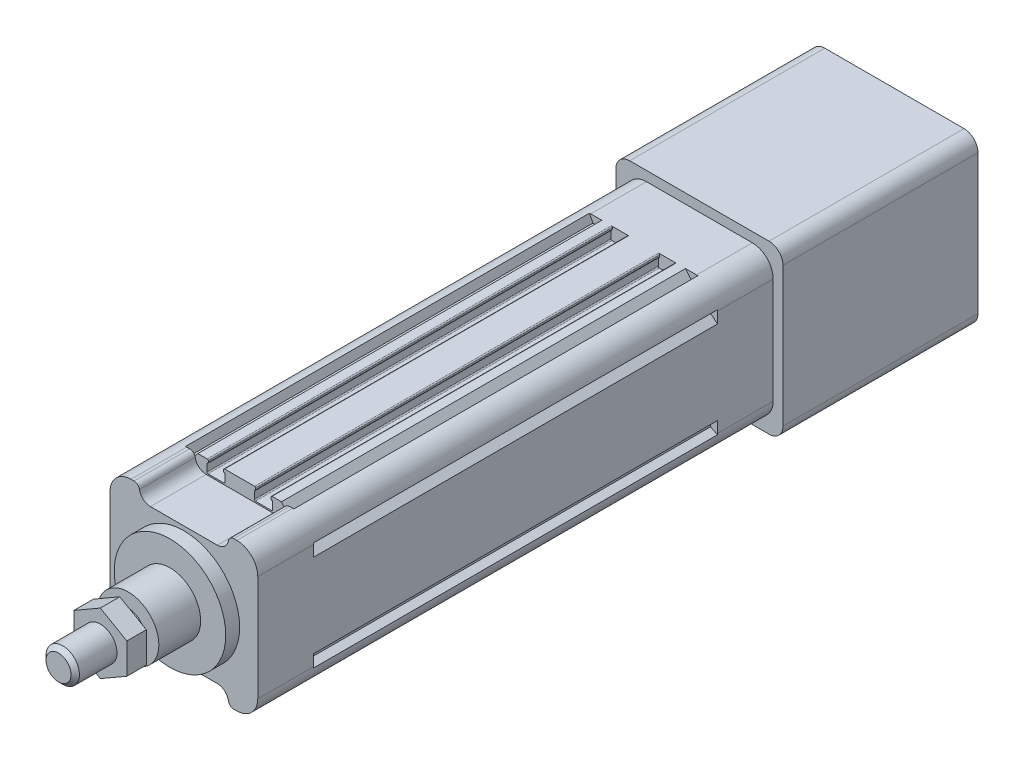
SolidWorks part; units mm, degrees
ref_plane "Front" through (0, 0, 0) normal (0, 0, 1) x (1, 0, 0)
ref_plane "Top" through (0, 0, 0) normal (0, 1, 0) x (1, 0, 0)
ref_plane "Right" through (0, 0, 0) normal (1, 0, 0) x (0, 0, -1)
sketch "草图1" plane through (0, 0, 0) normal (0, 0, 1) x (1, 0, 0)
  line L0 (19.7737, 3) -> (23.3, 3)
  line L1 (23.3, 3) -> (23.3, -3)
  line L2 (23.3, -3) -> (19.7737, -3)
  line L3 (-19.7737, -3) -> (-23.3, -3)
  line L4 (-23.3, -3) -> (-23.3, 3)
  line L5 (-23.3, 3) -> (-19.7737, 3)
  line L6 (-18.2, 24) -> (-19.4434, 26.4869)
  line L7 (-26.4869, 19.4434) -> (-24, 18.2)
  line L8 (-24, 18.2) -> (-24, 17.1)
  line L9 (-24, 17.1) -> (-26.5, 15)
  line L10 (-26.5, 15) -> (-26.5, -15)
  line L11 (-26.5, -15) -> (-24, -17.1)
  line L12 (-24, -17.1) -> (-24, -18.2)
  line L13 (-24, -18.2) -> (-26.4869, -19.4434)
  line L14 (-19.4434, -26.4869) -> (-18.2, -24)
  line L15 (-18.2, -24) -> (-17.1, -24)
  line L16 (-17.1, -24) -> (-15, -26.5)
  line L17 (-15, -26.5) -> (-11.65, -26.5)
  line L18 (-11.25, -26.1) -> (-11.25, -25.6)
  line L19 (-11.65, -25.2) -> (-11.75, -25.2)
  line L20 (-11.75, -25.2) -> (-11.75, -22.4)
  line L21 (-11.35, -22) -> (-5.65, -22)
  line L22 (-5.25, -22.4) -> (-5.25, -25.2)
  line L23 (-5.25, -25.2) -> (-5.35, -25.2)
  line L24 (-5.75, -25.6) -> (-5.75, -26.1)
  line L25 (-5.35, -26.5) -> (5.35, -26.5)
  line L26 (5.75, -26.1) -> (5.75, -25.6)
  line L27 (5.35, -25.2) -> (5.25, -25.2)
  line L28 (5.25, -25.2) -> (5.25, -22.4)
  line L29 (5.65, -22) -> (11.35, -22)
  line L30 (11.75, -22.4) -> (11.75, -25.2)
  line L31 (11.75, -25.2) -> (11.65, -25.2)
  line L32 (11.25, -25.6) -> (11.25, -26.1)
  line L33 (11.65, -26.5) -> (15, -26.5)
  line L34 (15, -26.5) -> (17.1, -24)
  line L35 (17.1, -24) -> (18.2, -24)
  line L36 (18.2, -24) -> (19.4434, -26.4869)
  line L37 (26.4869, -19.4434) -> (24, -18.2)
  line L38 (24, -18.2) -> (24, -17.1)
  line L39 (24, -17.1) -> (26.5, -15)
  line L40 (26.5, -15) -> (26.5, 15)
  line L41 (26.5, 15) -> (24, 17.1)
  line L42 (24, 17.1) -> (24, 18.2)
  line L43 (24, 18.2) -> (26.4869, 19.4434)
  line L44 (19.4434, 26.4869) -> (18.2, 24)
  line L45 (18.2, 24) -> (17.1, 24)
  line L46 (17.1, 24) -> (15, 26.5)
  line L47 (15, 26.5) -> (11.65, 26.5)
  line L48 (11.25, 26.1) -> (11.25, 25.6)
  line L49 (11.65, 25.2) -> (11.75, 25.2)
  line L50 (11.75, 25.2) -> (11.75, 22.4)
  line L51 (11.35, 22) -> (5.65, 22)
  line L52 (5.25, 22.4) -> (5.25, 25.2)
  line L53 (5.25, 25.2) -> (5.35, 25.2)
  line L54 (5.75, 25.6) -> (5.75, 26.1)
  line L55 (5.35, 26.5) -> (-5.35, 26.5)
  line L56 (-5.75, 26.1) -> (-5.75, 25.6)
  line L57 (-5.35, 25.2) -> (-5.25, 25.2)
  line L58 (-5.25, 25.2) -> (-5.25, 22.4)
  line L59 (-5.65, 22) -> (-11.35, 22)
  line L60 (-11.75, 22.4) -> (-11.75, 25.2)
  line L61 (-11.75, 25.2) -> (-11.65, 25.2)
  line L62 (-11.25, 25.6) -> (-11.25, 26.1)
  line L63 (-11.65, 26.5) -> (-15, 26.5)
  line L64 (-15, 26.5) -> (-17.1, 24)
  line L65 (-17.1, 24) -> (-18.2, 24)
  arc A0 (19.7737, 3) -> (-19.7737, 3) centre (0, 0) ccw
  arc A1 (-19.7737, -3) -> (19.7737, -3) centre (0, 0) ccw
  circle A2 centre (19, 19) radius 2.1
  circle A3 centre (19, -19) radius 2.1
  circle A4 centre (-19, -19) radius 2.1
  circle A5 centre (-19, 19) radius 2.1
  arc A6 (-19.4434, 26.4869) -> (-26.4869, 19.4434) centre (-19, 19) ccw
  arc A7 (-26.4869, -19.4434) -> (-19.4434, -26.4869) centre (-19, -19) ccw
  arc A8 (-11.65, -26.5) -> (-11.25, -26.1) centre (-11.65, -26.1) ccw
  arc A9 (-11.25, -25.6) -> (-11.65, -25.2) centre (-11.65, -25.6) ccw
  arc A10 (-11.35, -22) -> (-11.75, -22.4) centre (-11.35, -22.4) ccw
  arc A11 (-5.25, -22.4) -> (-5.65, -22) centre (-5.65, -22.4) ccw
  arc A12 (-5.35, -25.2) -> (-5.75, -25.6) centre (-5.35, -25.6) ccw
  arc A13 (-5.75, -26.1) -> (-5.35, -26.5) centre (-5.35, -26.1) ccw
  arc A14 (5.35, -26.5) -> (5.75, -26.1) centre (5.35, -26.1) ccw
  arc A15 (5.75, -25.6) -> (5.35, -25.2) centre (5.35, -25.6) ccw
  arc A16 (5.65, -22) -> (5.25, -22.4) centre (5.65, -22.4) ccw
  arc A17 (11.75, -22.4) -> (11.35, -22) centre (11.35, -22.4) ccw
  arc A18 (11.65, -25.2) -> (11.25, -25.6) centre (11.65, -25.6) ccw
  arc A19 (11.25, -26.1) -> (11.65, -26.5) centre (11.65, -26.1) ccw
  arc A20 (19.4434, -26.4869) -> (26.4869, -19.4434) centre (19, -19) ccw
  arc A21 (26.4869, 19.4434) -> (19.4434, 26.4869) centre (19, 19) ccw
  arc A22 (11.65, 26.5) -> (11.25, 26.1) centre (11.65, 26.1) ccw
  arc A23 (11.25, 25.6) -> (11.65, 25.2) centre (11.65, 25.6) ccw
  arc A24 (11.35, 22) -> (11.75, 22.4) centre (11.35, 22.4) ccw
  arc A25 (5.25, 22.4) -> (5.65, 22) centre (5.65, 22.4) ccw
  arc A26 (5.35, 25.2) -> (5.75, 25.6) centre (5.35, 25.6) ccw
  arc A27 (5.75, 26.1) -> (5.35, 26.5) centre (5.35, 26.1) ccw
  arc A28 (-5.35, 26.5) -> (-5.75, 26.1) centre (-5.35, 26.1) ccw
  arc A29 (-5.75, 25.6) -> (-5.35, 25.2) centre (-5.35, 25.6) ccw
  arc A30 (-5.65, 22) -> (-5.25, 22.4) centre (-5.65, 22.4) ccw
  arc A31 (-11.75, 22.4) -> (-11.35, 22) centre (-11.35, 22.4) ccw
  arc A32 (-11.65, 25.2) -> (-11.25, 25.6) centre (-11.65, 25.6) ccw
  arc A33 (-11.25, 26.1) -> (-11.65, 26.5) centre (-11.65, 26.1) ccw
extrude "凸台-拉伸1" add sketch "草图1" along normal blind 145
sketch "草图6" plane through (0, 0, 145) normal (0, 0, 1) x (1, 0, 0)
  line L0 (0, 0) -> (19, 0) construction
  line L2 (-26.5, -19) -> (-26.5, 19)
  line L3 (-19, 26.5) -> (-17.9161, 26.5)
  line L4 (26.5, -19) -> (26.5, 19)
  line L5 (-26.5, -26.5) -> (26.5, 26.5) construction
  line L6 (-26.5, 26.5) -> (26.5, -26.5) construction
  line L7 (-12, 21.5) -> (12, 21.5)
  line L9 (19, 26.5) -> (17.9161, 26.5)
  line L10 (19, -26.5) -> (17.9161, -26.5)
  line L11 (-12, -21.5) -> (12, -21.5)
  line L12 (-19, -26.5) -> (-17.9161, -26.5)
  arc A0 (12, 21.5) -> (15.9441, 24.8333) centre (12, 25.5) ccw
  arc A1 (-15.9441, 24.8333) -> (-12, 21.5) centre (-12, 25.5) ccw
  arc A2 (-15.9441, 24.8333) -> (-17.9161, 26.5) centre (-17.9161, 24.5) ccw
  arc A3 (15.9441, 24.8333) -> (17.9161, 26.5) centre (17.9161, 24.5) cw
  arc A4 (-26.5, -19) -> (-19, -26.5) centre (-19, -19) ccw
  arc A5 (19, -26.5) -> (26.5, -19) centre (19, -19) ccw
  arc A6 (26.5, 19) -> (19, 26.5) centre (19, 19) ccw
  arc A7 (-26.5, 19) -> (-19, 26.5) centre (-19, 19) cw
  arc A8 (15.9441, -24.8333) -> (17.9161, -26.5) centre (17.9161, -24.5) ccw
  arc A9 (12, -21.5) -> (15.9441, -24.8333) centre (12, -25.5) cw
  arc A10 (-15.9441, -24.8333) -> (-12, -21.5) centre (-12, -25.5) cw
  arc A11 (-15.9441, -24.8333) -> (-17.9161, -26.5) centre (-17.9161, -24.5) cw
  point P0 (0, 0)
  point P9 (0, 21.5)
  point P13 (20, 20.8461)
  point P16 (-12, 20.8461)
  dimension "D5" = 4
  dimension "D6" = 2
  dimension "D7" = 2
  dimension "D9" = 7.5
  dimension "D1" = 53
  dimension "D2" = 53
  dimension "D3" = 26.5
  dimension "D4" = 24
  dimension "D8" = 5
extrude "凸台-拉伸2" add sketch "草图6" along normal blind 20
sketch "草图7" plane through (0, 0, 165) normal (0, 0, 1) x (1, 0, 0)
  circle A0 centre (0, 0) radius 20
  dimension "D1" = 40
extrude "凸台-拉伸3" add sketch "草图7" along normal blind 5
sketch "草图9" plane through (0, 0, 170) normal (0, 0, 1) x (1, 0, 0)
  circle A0 centre (0, 0) radius 11
  dimension "D1" = 22
extrude "凸台-拉伸4" add sketch "草图9" along normal blind 15
sketch "草图10" plane through (0, 0, 185) normal (0, 0, 1) x (1, 0, 0)
  circle A0 centre (0, 0) radius 6
  dimension "D1" = 12
extrude "凸台-拉伸5" add sketch "草图10" along normal blind 25
sketch "草图11" plane through (0, 0, 0) normal (0, 0, -1) x (-1, 0, 0)
  line L1 (-19, -26.5) -> (19, -26.5)
  line L2 (-26.5, -19) -> (-26.5, 19)
  line L3 (-19, 26.5) -> (19, 26.5)
  line L4 (26.5, -19) -> (26.5, 19)
  line L5 (-26.5, -26.5) -> (26.5, 26.5) construction
  line L6 (-26.5, 26.5) -> (26.5, -26.5) construction
  arc A0 (-26.5, -19) -> (-19, -26.5) centre (-19, -19) ccw
  arc A1 (19, -26.5) -> (26.5, -19) centre (19, -19) ccw
  arc A2 (26.5, 19) -> (19, 26.5) centre (19, 19) ccw
  arc A3 (-26.5, 19) -> (-19, 26.5) centre (-19, 19) cw
  point P0 (0, 0)
  dimension "D3" = 7.5
  dimension "D1" = 53
  dimension "D2" = 53
extrude "凸台-拉伸6" add sketch "草图11" along normal blind 20
sketch "草图12" plane through (0, 0, -20) normal (0, 0, -1) x (-1, 0, 0)
  line L1 (-25, -30) -> (25, -30)
  line L2 (-30, -25) -> (-30, 25)
  line L3 (-25, 30) -> (25, 30)
  line L4 (30, -25) -> (30, 25)
  line L5 (-30, -30) -> (30, 30) construction
  line L6 (-30, 30) -> (30, -30) construction
  arc A0 (-30, -25) -> (-25, -30) centre (-25, -25) ccw
  arc A1 (25, -30) -> (30, -25) centre (25, -25) ccw
  arc A2 (30, 25) -> (25, 30) centre (25, 25) ccw
  arc A3 (-30, 25) -> (-25, 30) centre (-25, 25) cw
  point P0 (0, 0)
  dimension "D3" = 5
  dimension "D1" = 60
  dimension "D2" = 60
extrude "凸台-拉伸7" add sketch "草图12" along normal blind 70
sketch "草图14" plane through (0, 0, -90) normal (0, 0, -1) x (-1, 0, 0)
  circle A0 centre (0, 0) radius 19
  dimension "D1" = 38
extrude "切除-拉伸2" cut sketch "草图14" against normal blind 70
hole_wizard "M6 螺纹孔1" positions "草图15" profile "草图16" tap size "M6" standard "GB"
sketch "草图15" plane through (-26.5, 0, 0) normal (-1, 0, 0) x (0, 0, 1)
  line L0 (-20, -25) -> (-20, 25) construction
  line L1 (165, 19) -> (165, -19) construction
  point P0 (155, 11)
  point P2 (155, -11)
  point P4 (-10, 11)
  point P6 (-10, -11)
  dimension "D1" = 10
  dimension "D2" = 10
  dimension "D3" = 11
  dimension "D4" = 11
  dimension "D5" = 10
  dimension "D6" = 10
  dimension "D7" = 22
  dimension "D8" = 11
sketch "草图16" plane through (-26.5, 11, 155) normal (0, 1, 0) x (0, 0, 1)
  line L0 (0, 0) -> (0, 16.5022)
  line L1 (0, 16.5022) -> (2.5, 15)
  line L2 (2.5, 15) -> (2.5, 0)
  line L5 (2.5, 0) -> (0, 0)
  line L10 (0, 16.5022) -> (-2.5, 15) construction
  line L11 (0, -6.35) -> (0, 107.95) construction
  dimension "螺纹孔钻头直径" = 5
  dimension "螺纹孔钻头深度" = 15
  dimension "导头角度" = 118
cosmetic thread "孔螺蚊线4" parameters "D1"=12, "D2"=6
cosmetic thread "孔螺蚊线5" parameters "D1"=12, "D2"=6
cosmetic thread "孔螺蚊线6" parameters "D1"=12, "D2"=6
cosmetic thread "孔螺蚊线7" parameters "D1"=12, "D2"=6
chamfer "倒角1" distance 1.5 angle 45 1 edges at (6, 0, 210)
sketch "草图17" plane through (0, 0, 185) normal (0, 0, 1) x (1, 0, 0)
  line L1 (0, 10.9697) -> (-9.5, 5.4848)
  line L2 (-9.5, 5.4848) -> (-9.5, -5.4848)
  line L3 (-9.5, -5.4848) -> (0, -10.9697)
  line L4 (0, -10.9697) -> (9.5, -5.4848)
  line L5 (9.5, -5.4848) -> (9.5, 5.4848)
  line L6 (9.5, 5.4848) -> (0, 10.9697)
  circle A0 centre (0, 0) radius 9.5 construction
  dimension "D1" = 19
extrude "凸台-拉伸8" add sketch "草图17" along normal blind 7 from offset 3
